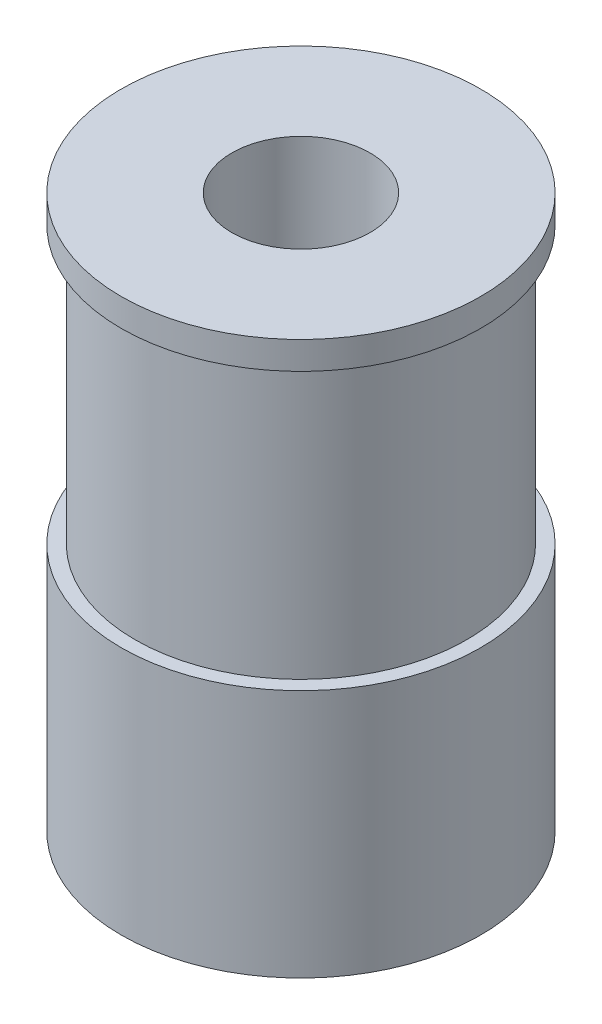
SolidWorks part; units mm, degrees
ref_plane "Спереди" through (0, 0, 0) normal (0, 0, 1) x (1, 0, 0)
ref_plane "Сверху" through (0, 0, 0) normal (0, 1, 0) x (1, 0, 0)
ref_plane "Справа" through (0, 0, 0) normal (1, 0, 0) x (0, 0, -1)
sketch "Sketch1" plane through (0, 0, 0) normal (0, 1, 0) x (1, 0, 0)
  circle A0 centre (0, 0) radius 6.5
  circle A1 centre (0, 0) radius 2.5
  dimension "D1" = 13
  dimension "D2" = 5
extrude "Boss-Extrude1" add sketch "Sketch1" along normal blind 20
ref_plane "Plane1" through (0, 19, 0) normal (0, 1, 0) x (1, 0, 0)
sketch "Sketch2" plane through (0, 19, 0) normal (0, 1, 0) x (1, 0, 0)
  circle A0 centre (0, 0) radius 6.7932
  circle A1 centre (0, 0) radius 6
  dimension "D1" = 12
extrude "Cut-Extrude1" cut sketch "Sketch2" against normal blind 10
